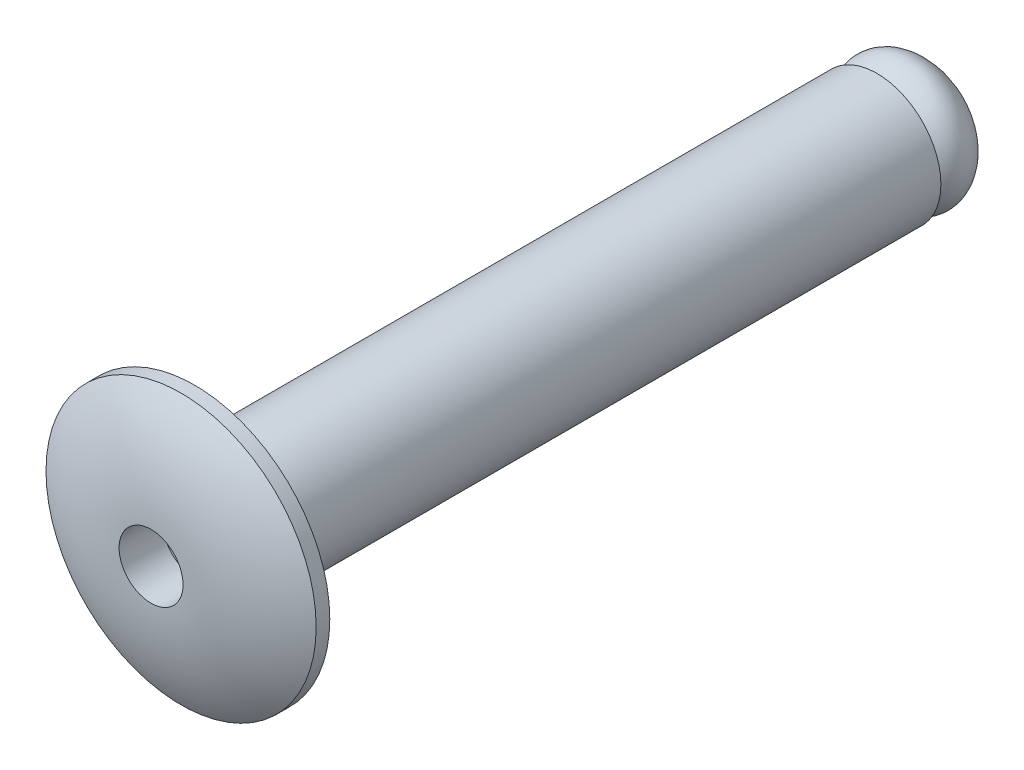
SolidWorks part; units mm, degrees
ref_plane "Front" through (0, 0, 0) normal (0, 0, 1) x (1, 0, 0)
ref_plane "Top" through (0, 0, 0) normal (0, 1, 0) x (1, 0, 0)
ref_plane "Right" through (0, 0, 0) normal (1, 0, 0) x (0, 0, -1)
sketch "Sketch1" plane through (0, 0, 0) normal (1, 0, 0) x (0, 0, -1)
  line L0 (-19.8628, 0) -> (-0.8128, 0) construction
  line L1 (-0.8128, 0) -> (0, 0) construction
  line L2 (0, 0) -> (12.7, 0) construction
  line L3 (12.7, 0) -> (13.9192, 0) construction
  line L8 (0, 2.5146) -> (0, -2.5146) construction
  line L9 (12.7, 1.1906) -> (12.7, -1.1906) construction
  dimension "length" = 12.7
  dimension "Head Height" = 0.8128
  dimension "D5" = 1.2192
  dimension "Dia" = 2.3813
  dimension "Head Diameter" = 5.0292
sketch "Sketch2" plane through (0, 0, 0) normal (1, 0, 0) x (0, 0, -1)
  line L0 (-19.8628, 0) -> (-19.8628, 0.5953)
  line L1 (-19.8628, 0.5953) -> (0, 0.5953) construction
  line L2 (0, 2.5146) -> (0, -2.5146) construction
  line L3 (0, 0) -> (0, 2.5146) construction
  line L4 (-0.8128, 0) -> (-0.8128, -1.8472) construction
  line L5 (12.7, 1.1906) -> (0, 1.1906)
  line L6 (12.7, 1.1906) -> (12.7, 0.893) construction
  line L7 (13.9192, 0) -> (13.9192, 1.1906) construction
  line L8 (12.7, 1.1906) -> (12.7, 0.893)
  line L9 (13.9192, 1.1906) -> (12.7, 1.1906) construction
  line L10 (12.7, 0) -> (13.9192, 0) construction
  line L11 (12.7, 0) -> (13.9192, 0)
  line L12 (-19.8628, 0) -> (12.7, 0)
  line L13 (-0.8128, 0.5953) -> (-0.8128, 0) construction
  line L14 (12.7, 1.1906) -> (12.7, 0) construction
  line L15 (12.7, 1.1906) -> (12.7, 0.893) construction
  line L16 (12.7, 0.893) -> (12.7, 0.5953) construction
  line L17 (12.7, 0.5953) -> (12.7, 0.2977) construction
  line L18 (12.7, 0.2977) -> (12.7, 0) construction
  line L19 (0, 1.1906) -> (0, 2.5146)
  line L20 (-0.8128, 0.5953) -> (-19.8628, 0.5953)
  line L22 (0, 2.5146) -> (-0.254, 2.5146)
  arc A2 (-0.254, 2.5146) -> (-0.8128, 0.5953) centre (2.7626, 0.5953) ccw
  ellipse E0 centre (13.1854, 0) end of major axis (13.1854, 1.1906) minor radius 0.7338 (13.9192, 0) -> (12.7, 0.893) ccw
  dimension "D3" = 0.254
  dimension "D1" = 0.5953
  dimension "D2" = 1.1906
revolve "Revolve1" add sketch "Sketch2" angle 360 about L12
sketch "Sketch3" plane through (0, 0, 0) normal (0, 1, 0) x (1, 0, 0)
  line L0 (0, -19.8628) -> (0.7985, -18.8222)
  line L1 (-0.5953, -19.8628) -> (0.5953, -19.8628) construction
  line L3 (0, -19.8628) -> (0, -20.3708) construction
  line L4 (0, -19.8628) -> (-0.7985, -18.8222)
  line L5 (-0.7985, -18.8222) -> (-0.7985, -20.3708)
  line L6 (-0.7985, -20.3708) -> (0.7985, -20.3708)
  line L7 (0.7985, -20.3708) -> (0.7985, -18.8222)
  dimension "D1" = 75
  dimension "D2" = 0.2032
  dimension "D3" = 0.508
extrude "Cut-Extrude1" cut sketch "Sketch3" against normal through all both and the other way through all
sketch "Sketch4" plane through (0, 0, 0) normal (1, 0, 0) x (0, 0, -1)
  line L0 (-19.8628, 0) -> (-20.3708, 0) construction
  line L1 (-19.8628, -0.5953) -> (-19.8628, 0.5953) construction
  line L2 (-20.1168, 0) -> (-19.0135, 1.1033)
  line L3 (-20.1168, 0) -> (-19.0135, -1.1033)
  line L4 (-19.0135, 1.1033) -> (-20.3708, 1.1033)
  line L5 (-20.3708, 1.1033) -> (-20.3708, -1.1033)
  line L6 (-20.3708, -1.1033) -> (-19.0135, -1.1033)
  dimension "D1" = 0.508
  dimension "D2" = 0.508
  dimension "D3" = 90
extrude "Cut-Extrude2" cut sketch "Sketch4" against normal through all both and the other way through all
fillet "Fillet2" radius 0.254 1 edges at (1.1906, 0, 0)
sketch "Sketch6" plane through (0, 0, 0) normal (1, 0, 0) x (0, 0, -1)
  line L0 (-5.7277, 0.5953) -> (-5.5753, 0.5953)
  line L1 (-19.8628, 0) -> (-0.8128, 0) construction
  line L2 (-5.5753, 0.5953) -> (-5.5753, -0.5953) construction
  line L3 (-19.8628, -0.254) -> (-19.8628, 0.254) construction
  line L4 (-0.8128, 0.5953) -> (-0.8128, -0.5953) construction
  line L5 (-19.5215, -0.5953) -> (-0.8128, -0.5953) construction
  arc A0 (-5.7277, 0.5953) -> (-5.5753, 0.5953) centre (-5.6515, 0.5953) ccw
  point P23 (-5.5753, 0)
  dimension "D2" = 0.0762
  dimension "D1" = 14.2875
  dimension "D3" = 19.05
revolve "Cut-Revolve1" [suppressed] cut sketch "Sketch6" angle 360 about L1
pattern_linear "LPattern1" [suppressed] count 12 spacing 0.762 along (0, 0, -1)
sketch "Sketch7" plane through (0, 0, 0) normal (0, 0, -1) x (-1, 0, 0)
  circle A0 centre (0, 0) radius 0.5953
extrude "Cut-Extrude3" cut sketch "Sketch7" against normal through all
equation "\"D5@Sketch1\" = \"Head Height@Sketch1\" * 1.5"
equation "\"D9@Sketch1\" = \"length@Sketch1\" * 1.5"
equation "\"D1@Sketch2\"=\"D2@Sketch2\"/2"
equation "\"D1@Sketch6\"=\"D3@Sketch6\"*.75"
